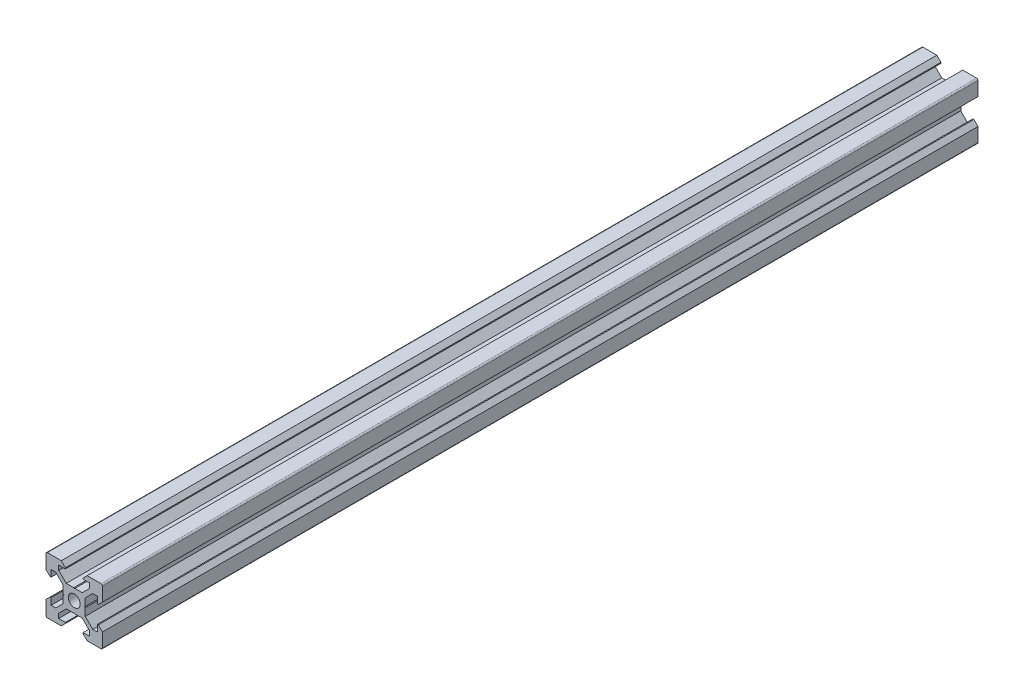
SolidWorks part; units mm, degrees
material "6061-T6 (SS)"
ref_plane "Front Plane" through (0, 0, 0) normal (0, 0, 1) x (1, 0, 0)
ref_plane "Top Plane" through (0, 0, 0) normal (0, 1, 0) x (1, 0, 0)
ref_plane "Right Plane" through (0, 0, 0) normal (1, 0, 0) x (0, 0, -1)
sketch "Sketch1" plane through (0, 0, 0) normal (0, 0, 1) x (1, 0, 0)
  line L1 (9.5, -10) -> (-9.5, -10)
  line L2 (10, -9.5) -> (10, 9.5)
  line L3 (9.5, 10) -> (-9.5, 10)
  line L4 (-10, -9.5) -> (-10, 9.5)
  line L5 (10, -10) -> (-10, 10) construction
  line L6 (10, 10) -> (-10, -10) construction
  circle A0 centre (0, 0) radius 2.1
  arc A1 (-9.5, 10) -> (-10, 9.5) centre (-9.5, 9.5) ccw
  arc A2 (10, 9.5) -> (9.5, 10) centre (9.5, 9.5) ccw
  arc A3 (9.5, -10) -> (10, -9.5) centre (9.5, -9.5) ccw
  arc A4 (-9.5, -10) -> (-10, -9.5) centre (-9.5, -9.5) cw
  point P0 (0, 0)
  line B0 (0, 0) -> (0, 10) construction
  line B1 (0, 3.69) -> (-0.21, 3.9)
  line B2 (-0.21, 3.9) -> (-2.8393, 3.9)
  line B3 (-2.8393, 3.9) -> (-5.5, 6.5607)
  line B4 (-5.5, 6.5607) -> (-5.5, 8.2)
  line B5 (-5.5, 8.2) -> (-3.125, 8.2)
  line B6 (-3.125, 8.2) -> (-3.125, 8.545)
  line B7 (-3.125, 8.545) -> (-4.58, 10)
  line B8 (-4.58, 10) -> (4.58, 10)
  line B9 (0, 0) -> (-5.9132, 5.9132) construction
  line B10 (3.125, 8.545) -> (4.58, 10)
  line B11 (3.125, 8.2) -> (3.125, 8.545)
  line B12 (5.5, 8.2) -> (3.125, 8.2)
  line B13 (5.5, 6.5607) -> (5.5, 8.2)
  line B14 (2.8393, 3.9) -> (5.5, 6.5607)
  line B15 (0.21, 3.9) -> (2.8393, 3.9)
  line B16 (0, 3.69) -> (0.21, 3.9)
  line B17 (0, 0) -> (-10, 0) construction
  line B18 (-3.69, 0) -> (-3.9, -0.21)
  line B19 (-3.9, -0.21) -> (-3.9, -2.8393)
  line B20 (-3.9, -2.8393) -> (-6.5607, -5.5)
  line B21 (-6.5607, -5.5) -> (-8.2, -5.5)
  line B22 (-8.2, -5.5) -> (-8.2, -3.125)
  line B23 (-8.2, -3.125) -> (-8.545, -3.125)
  line B24 (-8.545, -3.125) -> (-10, -4.58)
  line B25 (-10, -4.58) -> (-10, 4.58)
  line B26 (0, 0) -> (-5.9132, -5.9132) construction
  line B27 (-8.545, 3.125) -> (-10, 4.58)
  line B28 (-8.2, 3.125) -> (-8.545, 3.125)
  line B29 (-8.2, 5.5) -> (-8.2, 3.125)
  line B30 (-6.5607, 5.5) -> (-8.2, 5.5)
  line B31 (-3.9, 2.8393) -> (-6.5607, 5.5)
  line B32 (-3.9, 0.21) -> (-3.9, 2.8393)
  line B33 (-3.69, 0) -> (-3.9, 0.21)
  line B34 (0, 0) -> (0, -10) construction
  line B35 (0, -3.69) -> (0.21, -3.9)
  line B36 (0.21, -3.9) -> (2.8393, -3.9)
  line B37 (2.8393, -3.9) -> (5.5, -6.5607)
  line B38 (5.5, -6.5607) -> (5.5, -8.2)
  line B39 (5.5, -8.2) -> (3.125, -8.2)
  line B40 (3.125, -8.2) -> (3.125, -8.545)
  line B41 (3.125, -8.545) -> (4.58, -10)
  line B42 (4.58, -10) -> (-4.58, -10)
  line B43 (0, 0) -> (5.9132, -5.9132) construction
  line B44 (-3.125, -8.545) -> (-4.58, -10)
  line B45 (-3.125, -8.2) -> (-3.125, -8.545)
  line B46 (-5.5, -8.2) -> (-3.125, -8.2)
  line B47 (-5.5, -6.5607) -> (-5.5, -8.2)
  line B48 (-2.8393, -3.9) -> (-5.5, -6.5607)
  line B49 (-0.21, -3.9) -> (-2.8393, -3.9)
  line B50 (0, -3.69) -> (-0.21, -3.9)
  line B51 (0, 0) -> (10, 0) construction
  line B52 (3.69, 0) -> (3.9, 0.21)
  line B53 (3.9, 0.21) -> (3.9, 2.8393)
  line B54 (3.9, 2.8393) -> (6.5607, 5.5)
  line B55 (6.5607, 5.5) -> (8.2, 5.5)
  line B56 (8.2, 5.5) -> (8.2, 3.125)
  line B57 (8.2, 3.125) -> (8.545, 3.125)
  line B58 (8.545, 3.125) -> (10, 4.58)
  line B59 (10, 4.58) -> (10, -4.58)
  line B60 (0, 0) -> (5.9132, 5.9132) construction
  line B61 (8.545, -3.125) -> (10, -4.58)
  line B62 (8.2, -3.125) -> (8.545, -3.125)
  line B63 (8.2, -5.5) -> (8.2, -3.125)
  line B64 (6.5607, -5.5) -> (8.2, -5.5)
  line B65 (3.9, -2.8393) -> (6.5607, -5.5)
  line B66 (3.9, -0.21) -> (3.9, -2.8393)
  line B67 (3.69, 0) -> (3.9, -0.21)
  dimension "D1" = 4.2
  dimension "D3" = 0.5
  dimension "D2" = 20
sketch_block_instance "V Slot 1-4"
sketch_block "V Slot 1" parameters "D1"=10, "D2"=11, "D3"=4.3, "D4"=1.8, "D5"=0.21, "D6"=45, "D7"=9.16, "D8"=1.5, "D9"=6.25
sketch_block_instance "V Slot 1-5"
sketch_block_instance "V Slot 1-6"
sketch_block_instance "V Slot 1-7"
extrude "Boss-Extrude1" add sketch "Sketch1" along normal blind 500 contours B67 B52 B53 B54 B55 B56 B57 B58 L2 A2 L3 B10 B11 B12 B13 B14 B15 B16 B1 B2 B3 B4 B5 B6 B7 A1 L4 B27 B28 B29 B30 B31 B32 B33 B18 B19 B20 B21 B22 B23 B24 A4 L1 B44 B45 B46 B47 B48 B49
sketch "Sketch2" plane through (0, 0, 500) normal (0, 0, 1) x (1, 0, 0)
  line L1 (-28.5697, 18.4094) -> (25.7732, 18.4094)
  line L2 (-28.5697, 18.4094) -> (-28.5697, -27.0318)
  line L3 (-28.5697, -27.0318) -> (25.7732, -27.0318)
  line L4 (25.7732, 18.4094) -> (25.7732, -27.0318)
extrude "Cut-Extrude1" cut sketch "Sketch2" against normal blind 189.7888
